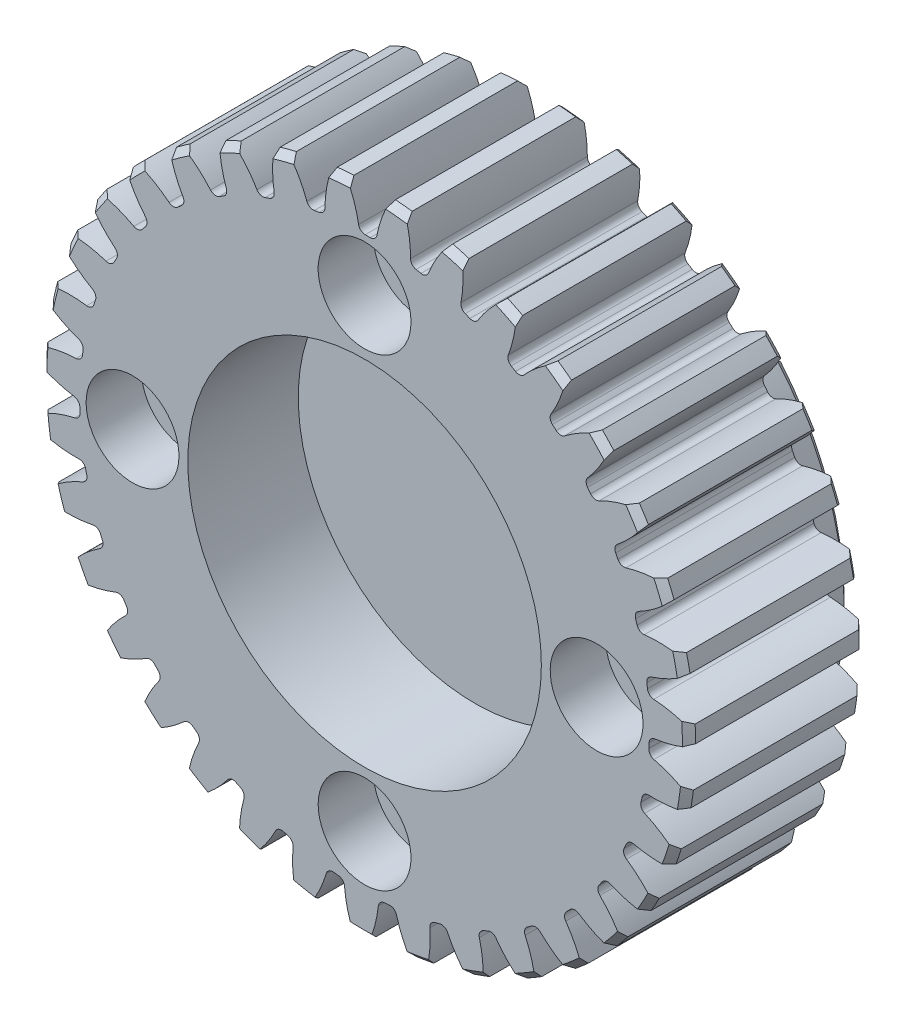
SolidWorks part; units mm, degrees
ref_plane "Front" through (0, 0, 0) normal (0, 0, 1) x (1, 0, 0)
ref_plane "Top" through (0, 0, 0) normal (0, 1, 0) x (1, 0, 0)
ref_plane "Right" through (0, 0, 0) normal (1, 0, 0) x (0, 0, -1)
sketch "Sketch3" plane through (0, 0, 0) normal (0, 0, 1) x (1, 0, 0)
  circle A0 centre (0, 0) radius 14.6844
  dimension "od" = 29.3687
extrude "gearBody" add sketch "Sketch3" along normal blind 8
chamfer "Chamfer2" distance 0.3 angle 45 2 edges at (14.6844, 0, 0) (14.6844, 0, 8)
sketch "Sketch2" plane through (0, 0, 0) normal (0, 0, 1) x (1, 0, 0)
  line L0 (0, 0) -> (12.4245, 5.1464) construction
  line L1 (16.6448, -3.9198) -> (0, 0) construction
  line L2 (0, 0) -> (36.3143, 0) construction
  line L3 (13.8896, -0.167) -> (13.8217, -1.3817) construction
  line L5 (13.8557, -0.7744) -> (0, 0) construction
  line L7 (0, 0) -> (13.4482, 0) construction
  arc A0 (13.4455, -0.2699) -> (13.3918, -1.23) centre (0, 0) ccw construction
  arc A1 (14.6839, 0.1191) -> (14.5792, -1.7545) centre (0, 0) ccw construction
  arc A2 (13.8896, -0.167) -> (13.8217, -1.3817) centre (0, 0) ccw construction
  arc A3 (12.8604, -0.8323) -> (12.8731, -0.6059) centre (0, 0) ccw
  arc A4 (16.6448, -3.9198) -> (13.0909, -1.1468) centre (11.7737, -6.4988) ccw
  arc A5 (16.6448, -3.9198) -> (16.9779, 2.0407) centre (0, 0) ccw
  arc A6 (16.9779, 2.0407) -> (13.1372, -0.319) centre (12.4245, 5.1464) cw
  arc A7 (12.8731, -0.6059) -> (13.1372, -0.319) centre (13.1764, -0.6202) cw
  arc A8 (13.0909, -1.1468) -> (12.8604, -0.8323) centre (13.1635, -0.8519) cw
  point P6 (16.9779, 2.0407)
  point P22 (16.6448, -3.9198)
  dimension "baseDia" = 26.8964
  dimension "od" = 29.3687
  dimension "pd" = 27.7812
  dimension "rd" = 25.7747
  dimension "rFillet" = 0.3037
  dimension "pointX" = 16.9779
  dimension "pointY" = 2.0407
  dimension "CTT" = 1.2148
  dimension "flankCenterAngle" = 22.5
extrude "toothCut" cut sketch "Sketch2" along normal through all
pattern_circular "CirPattern1" count 35 over 360 about axis through (0, 0, 0) along (0, 0, 1) of "toothCut"
sketch "hub1Dia" plane through (0, 0, 0) normal (0, 0, -1) x (-1, 0, 0)
  circle A0 centre (0, 0) radius 12.7
  dimension "hub1Dia" = 25.4
sketch "hub2Dia" plane through (0, 0, 8) normal (0, 0, 1) x (1, 0, 0)
  circle A0 centre (0, 0) radius 12.7
  dimension "hub2dia" = 25.4
sketch "Sketch4" plane through (0, 0, 0) normal (0, 0, -1) x (-1, 0, 0)
  line L0 (-9.5666, 8.2) -> (9.5666, 8.2)
  arc A0 (-9.5666, 8.2) -> (9.5666, 8.2) centre (0, 0) ccw
  dimension "D1" = 25.2
  dimension "D2" = 8.2
extrude "Boss-Extrude1" add sketch "Sketch4" along normal blind 1.4
chamfer "Chamfer1" distance 0.3 angle 45 2 edges at (0, 8.2, -1.4) (0, -12.6, -1.4)
sketch "Sketch5" plane through (0, 0, -1.4) normal (0, 0, -1) x (-1, 0, 0)
  circle A0 centre (0, -6) radius 2.1
  dimension "D1" = 4.2
  dimension "D2" = 6
extrude "Cut-Extrude1" cut sketch "Sketch5" against normal blind 2.2
sketch "Sketch6" plane through (0, 0, 8) normal (0, 0, 1) x (1, 0, 0)
  circle A0 centre (0, 0) radius 8
  dimension "D1" = 16
extrude "Cut-Extrude2" cut sketch "Sketch6" against normal blind 5
sketch "Sketch7" plane through (0, 0, 8) normal (0, 0, 1) x (1, 0, 0)
  circle A0 centre (0, 10.5) radius 2.1
  dimension "D1" = 4.2
  dimension "D2" = 10.5
extrude "Cut-Extrude3" cut sketch "Sketch7" against normal blind 2.5
pattern_circular "CirPattern2" count 4 over 360 about axis through (0, 0, 0) along (0, 0, 1) of "Cut-Extrude3"
